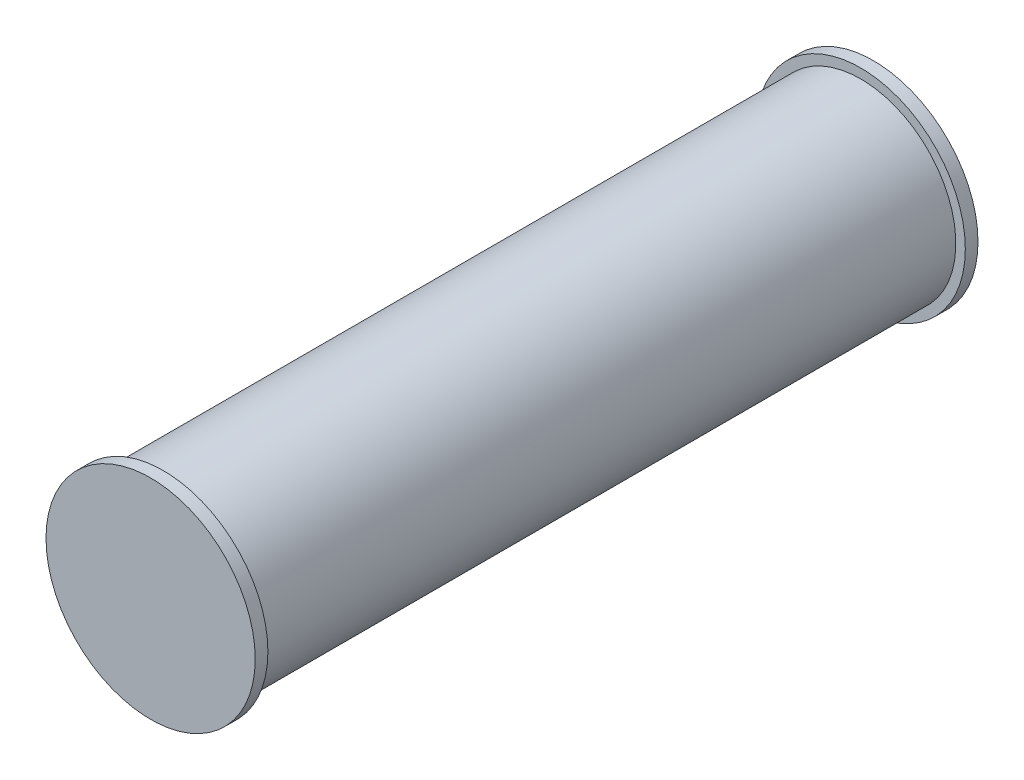
SolidWorks part; units mm, degrees
ref_plane "Plan de face" through (0, 0, 0) normal (0, 0, 1) x (1, 0, 0)
ref_plane "Plan de dessus" through (0, 0, 0) normal (0, 1, 0) x (1, 0, 0)
ref_plane "Plan de droite" through (0, 0, 0) normal (1, 0, 0) x (0, 0, -1)
sketch "Esquisse1" plane through (0, 0, 0) normal (0, 0, 1) x (1, 0, 0)
  circle A0 centre (0, 0) radius 15
  dimension "D1" = 30
extrude "Boss.-Extru.1" add sketch "Esquisse1" along normal blind 110
sketch "Esquisse2" plane through (0, 0, 0) normal (0, 0, -1) x (-1, 0, 0)
  circle A0 centre (0, 0) radius 16.5
  dimension "D1" = 33
extrude "Boss.-Extru.2" add sketch "Esquisse2" along normal blind 2
sketch "Esquisse3" plane through (0, 0, 110) normal (0, 0, 1) x (1, 0, 0)
  circle A0 centre (0, 0) radius 16.5
  dimension "D1" = 33
extrude "Boss.-Extru.3" add sketch "Esquisse3" along normal blind 2
